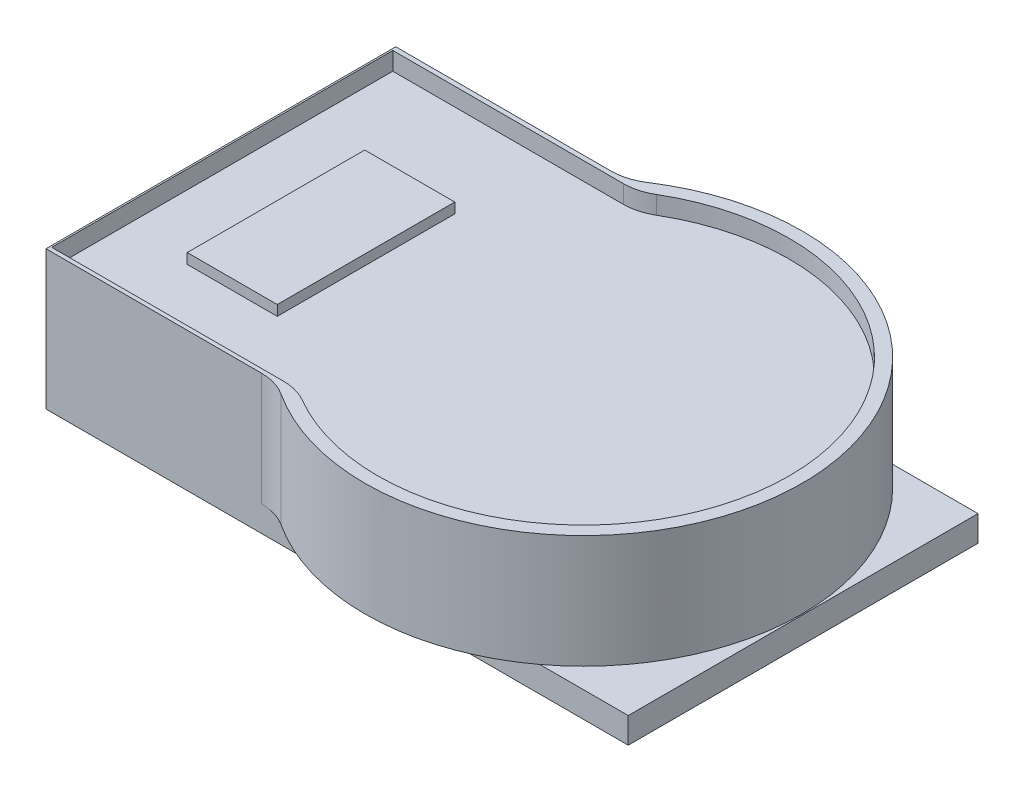
SolidWorks part; units mm, degrees
ref_plane "Front Plane" through (0, 0, 0) normal (0, 0, 1) x (1, 0, 0)
ref_plane "Top Plane" through (0, 0, 0) normal (0, 1, 0) x (1, 0, 0)
ref_plane "Right Plane" through (0, 0, 0) normal (1, 0, 0) x (0, 0, -1)
sketch "Sketch1" plane through (0, 0, 0) normal (0, 1, 0) x (1, 0, 0)
  line L1 (-70.5, 34) -> (-25.5, 34)
  line L2 (-70.5, 34) -> (-70.5, -34)
  line L3 (-70.5, -34) -> (-25.5, -34)
  arc A0 (-25.5, -34) -> (-25.5, 34) centre (0, 0) ccw
  dimension "D1" = 85
  dimension "D2" = 68
  dimension "D3" = 45
extrude "Boss-Extrude1" add sketch "Sketch1" along normal blind 22
fillet "Fillet1" radius 10 2 edges at (-25.5, 11, -34) (-25.5, 11, 34)
sketch "Sketch3" plane through (0, 22, 0) normal (0, 1, 0) x (1, 0, 0)
  line L6 (-22.4718, 33.091) -> (-70.1756, 33.091)
  line L8 (-22.2893, -33.2143) -> (-70.1756, -33.2143)
  line L9 (-70.1756, 33.091) -> (-70.1756, -33.2143)
  arc A0 (-22.2893, -33.2143) -> (-22.4718, 33.091) centre (0, 0) ccw
  dimension "D1" = 80
extrude "Cut-Extrude1" cut sketch "Sketch3" against normal blind 3.5
fillet "Fillet2" radius 10 2 edges at (-22.2893, 20.25, 33.2143) (-22.4718, 20.25, -33.091)
sketch "Sketch4" plane through (0, 18.5, 0) normal (0, 1, 0) x (1, 0, 0)
  line L1 (-57.6284, 15.0974) -> (-40.1277, 15.0974)
  line L2 (-57.6284, 15.0974) -> (-57.6284, -19.4109)
  line L3 (-57.6284, -19.4109) -> (-40.1277, -19.4109)
  line L4 (-40.1277, 15.0974) -> (-40.1277, -19.4109)
extrude "Boss-Extrude2" add sketch "Sketch4" along normal blind 2
sketch "Sketch5" plane through (0, 0, 0) normal (0, -1, 0) x (1, 0, 0)
  line L1 (-70.5, 34) -> (42.6923, 34)
  line L2 (-70.5, 34) -> (-70.5, -34)
  line L3 (-70.5, -34) -> (42.6923, -34)
  line L4 (42.6923, 34) -> (42.6923, -34)
extrude "Boss-Extrude3" add sketch "Sketch5" along normal blind 5
